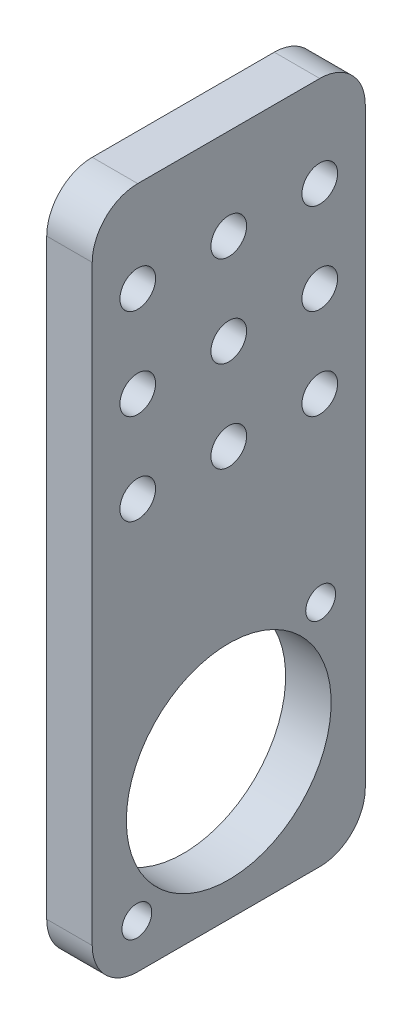
SolidWorks part; units mm, degrees
material "1060 Alloy"
ref_plane "Front Plane" through (0, 0, 0) normal (0, 0, 1) x (1, 0, 0)
ref_plane "Top Plane" through (0, 0, 0) normal (0, 1, 0) x (1, 0, 0)
ref_plane "Right Plane" through (0, 0, 0) normal (1, 0, 0) x (0, 0, -1)
ref_plane "Plane1" through (95.25, 0, 0) normal (1, 0, 0) x (0, 0, -1)
sketch "Sketch1" plane through (95.25, 0, 0) normal (1, 0, 0) x (0, 0, -1)
  line L0 (-184.15, -107.95) -> (-184.15, -25.4)
  line L1 (-190.5, -19.05) -> (-215.9, -19.05)
  line L2 (-222.25, -25.4) -> (-222.25, -107.95)
  line L3 (-215.9, -114.3) -> (-190.5, -114.3)
  circle A0 centre (-190.3762, -82.4262) radius 2.0828
  circle A1 centre (-216.0238, -108.0738) radius 2.0828
  circle A2 centre (-203.2, -95.25) radius 14.2875
  arc A3 (-184.15, -25.4) -> (-190.5, -19.05) centre (-190.5, -25.4) ccw
  arc A4 (-215.9, -19.05) -> (-222.25, -25.4) centre (-215.9, -25.4) ccw
  arc A5 (-222.25, -107.95) -> (-215.9, -114.3) centre (-215.9, -107.95) ccw
  arc A6 (-190.5, -114.3) -> (-184.15, -107.95) centre (-190.5, -107.95) ccw
  circle A7 centre (-215.9, -31.75) radius 2.4892
  circle A8 centre (-203.2, -31.75) radius 2.4892
  circle A9 centre (-190.5, -31.75) radius 2.4892
  circle A10 centre (-215.9, -57.15) radius 2.4892
  circle A11 centre (-203.2, -57.15) radius 2.4892
  circle A12 centre (-190.5, -57.15) radius 2.4892
  circle A13 centre (-215.9, -44.45) radius 2.4892
  circle A14 centre (-203.2, -44.45) radius 2.4892
  circle A15 centre (-190.5, -44.45) radius 2.4892
extrude "Boss-Extrude1" add sketch "Sketch1" against normal blind 6.35
